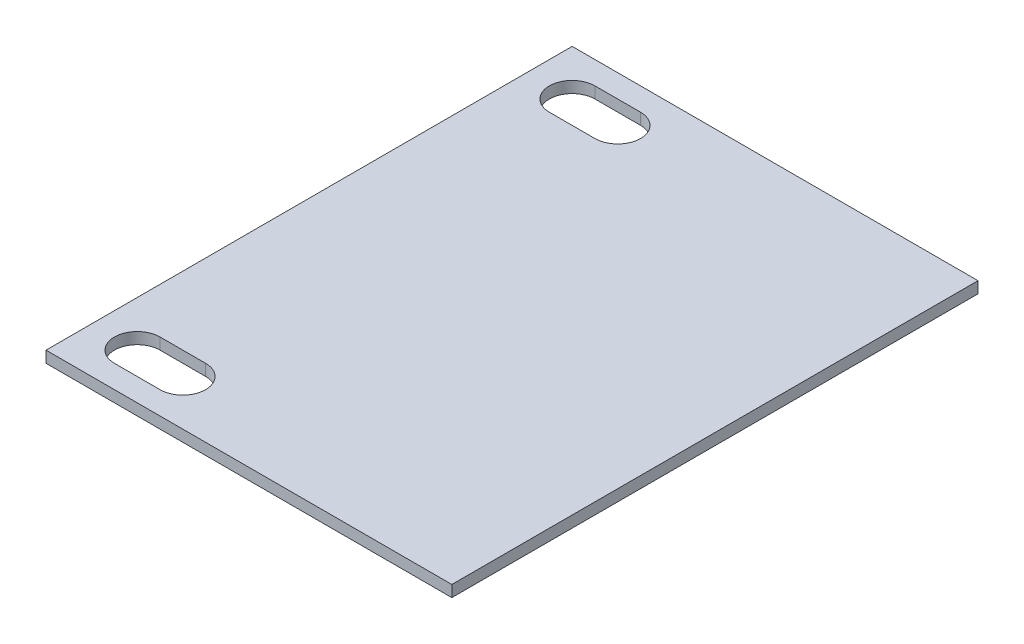
SolidWorks part; units mm, degrees
material "Acrylic (Medium-high impact)"
ref_plane "Front Plane" through (0, 0, 0) normal (0, 0, 1) x (1, 0, 0)
ref_plane "Top Plane" through (0, 0, 0) normal (0, 1, 0) x (1, 0, 0)
ref_plane "Right Plane" through (0, 0, 0) normal (1, 0, 0) x (0, 0, -1)
sketch "Sketch1" plane through (0, 0, 0) normal (0, 1, 0) x (1, 0, 0)
  line L1 (-113, -146.5) -> (113, -146.5)
  line L2 (-113, -146.5) -> (-113, 146.5)
  line L3 (-113, 146.5) -> (113, 146.5)
  line L4 (113, -146.5) -> (113, 146.5)
  line L5 (-113, -146.5) -> (113, 146.5) construction
  line L6 (-113, 146.5) -> (113, -146.5) construction
  point P0 (0, 0)
  dimension "D1" = 293
  dimension "D2" = 226
extrude "Main Base" add sketch "Sketch1" along normal mid plane 6.35
sketch "Sketch2" plane through (0, 3.175, 0) normal (0, 1, 0) x (1, 0, 0)
  line L0 (-87.6, 121.1) -> (-62.2, 121.1) construction
  line L1 (-87.6, 133.8) -> (-62.2, 133.8)
  line L2 (-87.6, 108.4) -> (-62.2, 108.4)
  line L3 (113, 146.5) -> (-113, 146.5) construction
  line L4 (-1000, 0) -> (49000, 0) construction
  line L5 (-87.6, -121.1) -> (-62.2, -121.1) construction
  line L6 (-87.6, -133.8) -> (-62.2, -133.8)
  line L7 (-87.6, -108.4) -> (-62.2, -108.4)
  line L8 (-113, 146.5) -> (-113, -146.5) construction
  arc A0 (-87.6, 133.8) -> (-87.6, 108.4) centre (-87.6, 121.1) ccw
  arc A1 (-62.2, 108.4) -> (-62.2, 133.8) centre (-62.2, 121.1) ccw
  arc A2 (-87.6, -133.8) -> (-87.6, -108.4) centre (-87.6, -121.1) cw
  arc A3 (-62.2, -108.4) -> (-62.2, -133.8) centre (-62.2, -121.1) cw
  point P2 (-74.9, 121.1)
  point P14 (-74.9, -121.1)
  point P19 (0, 0)
  dimension "D2" = 25.4
  dimension "D1" = 25.4
  dimension "D3" = 25.4
  dimension "D4" = 25.4
extrude "Handles" cut sketch "Sketch2" against normal through all
